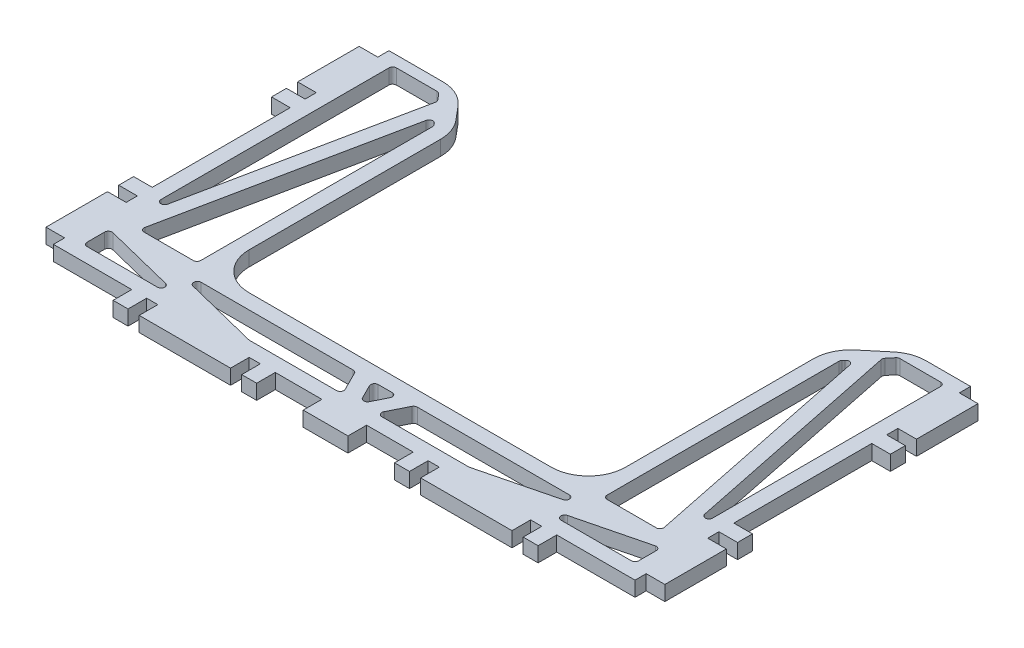
SolidWorks part; units mm, degrees
ref_plane "Front Plane" through (0, 0, 0) normal (0, 0, 1) x (1, 0, 0)
ref_plane "Top Plane" through (0, 0, 0) normal (0, 1, 0) x (1, 0, 0)
ref_plane "Right Plane" through (0, 0, 0) normal (1, 0, 0) x (0, 0, -1)
sketch "Sketch1" plane through (0, 0, 0) normal (0, 1, 0) x (1, 0, 0)
  line L0 (-78, 42.5) -> (-58.891, 42.5)
  line L1 (-58.891, 42.5) -> (-50.5, 32.5)
  line L2 (-50.5, 32.5) -> (-50.5, -32.5)
  line L3 (-50.5, -32.5) -> (50.5, -32.5)
  line L4 (50.5, -32.5) -> (50.5, 32.5)
  line L5 (50.5, 32.5) -> (62.4175, 42.5)
  line L6 (62.4175, 42.5) -> (78, 42.5)
  line L7 (78, 42.5) -> (78, -47.5)
  line L8 (78, -47.5) -> (-78, -47.5)
  line L9 (-78, -47.5) -> (-78, 42.5)
  line L10 (0, 42.5) -> (0, -47.5) construction
  line L11 (78, 39.5) -> (83, 39.5)
  line L12 (78, 39.5) -> (78, 23)
  line L13 (78, 23) -> (83, 23)
  line L14 (83, 39.5) -> (83, 23)
  line L15 (78, -28) -> (83, -28)
  line L16 (78, -28) -> (78, -44.5)
  line L17 (78, -44.5) -> (83, -44.5)
  line L18 (83, -28) -> (83, -44.5)
  line L19 (-6, -47.5) -> (-6, -52.5)
  line L20 (78, 20) -> (83, 20)
  line L21 (78, 20) -> (78, 16)
  line L22 (78, 16) -> (83, 16)
  line L23 (83, 20) -> (83, 16)
  line L24 (78, -25) -> (83, -25)
  line L25 (78, -25) -> (78, -21)
  line L26 (78, -21) -> (83, -21)
  line L27 (83, -25) -> (83, -21)
  line L28 (25.5, -47.5) -> (50, -47.5)
  line L29 (25.5, -47.5) -> (25.5, -52.5)
  line L30 (25.5, -52.5) -> (50, -52.5)
  line L31 (50, -47.5) -> (50, -52.5)
  line L32 (53, -47.5) -> (57, -47.5)
  line L33 (53, -47.5) -> (53, -52.5)
  line L34 (53, -52.5) -> (57, -52.5)
  line L35 (57, -47.5) -> (57, -52.5)
  line L36 (22.5, -47.5) -> (18.5, -47.5)
  line L37 (22.5, -47.5) -> (22.5, -52.5)
  line L38 (22.5, -52.5) -> (18.5, -52.5)
  line L39 (18.5, -47.5) -> (18.5, -52.5)
  line L40 (-6, -47.5) -> (6, -47.5)
  line L41 (0, -47.5) -> (0, -52.5)
  line L42 (-6, -52.5) -> (6, -52.5)
  line L43 (6, -47.5) -> (6, -52.5)
  line L44 (-22.5, -52.5) -> (-18.5, -52.5)
  line L45 (-18.5, -47.5) -> (-18.5, -52.5)
  line L46 (-22.5, -47.5) -> (-18.5, -47.5)
  line L47 (-22.5, -47.5) -> (-22.5, -52.5)
  line L48 (-25.5, -52.5) -> (-50, -52.5)
  line L49 (-50, -47.5) -> (-50, -52.5)
  line L50 (-25.5, -47.5) -> (-50, -47.5)
  line L51 (-25.5, -47.5) -> (-25.5, -52.5)
  line L52 (-53, -52.5) -> (-57, -52.5)
  line L53 (-57, -47.5) -> (-57, -52.5)
  line L54 (-53, -47.5) -> (-57, -47.5)
  line L55 (-53, -47.5) -> (-53, -52.5)
  line L56 (-78, -44.5) -> (-83, -44.5)
  line L57 (-83, -28) -> (-83, -44.5)
  line L58 (-78, -28) -> (-83, -28)
  line L59 (-78, -28) -> (-78, -44.5)
  line L60 (-78, -21) -> (-83, -21)
  line L61 (-83, -25) -> (-83, -21)
  line L62 (-78, -25) -> (-83, -25)
  line L63 (-78, -25) -> (-78, -21)
  line L64 (-78, 16) -> (-83, 16)
  line L65 (-83, 20) -> (-83, 16)
  line L66 (-78, 20) -> (-83, 20)
  line L67 (-78, 20) -> (-78, 16)
  line L68 (-78, 23) -> (-83, 23)
  line L69 (-83, 39.5) -> (-83, 23)
  line L70 (-78, 39.5) -> (-83, 39.5)
  line L71 (-78, 39.5) -> (-78, 23)
  line L72 (-74, 39.5) -> (-61.5953, 39.5)
  line L73 (-61.5953, 39.5) -> (-59.6881, 37.227)
  line L74 (-59.6881, 37.227) -> (-74, -32.5)
  line L75 (-74, -32.5) -> (-74, 39.5)
  line L76 (-56.4072, 33.3171) -> (-54.5, 31.0441)
  line L77 (-54.5, 31.0441) -> (-54.5, -32.5)
  line L78 (-54.5, -32.5) -> (-69.9166, -32.5)
  line L79 (-69.9166, -32.5) -> (-56.4072, 33.3171)
  line L80 (-74, -36.5) -> (-74, -43.5)
  line L81 (-74, -43.5) -> (-45.997, -43.5)
  line L82 (-45.997, -43.5) -> (-74, -36.5)
  line L83 (-57.5059, -36.5) -> (-7.9721, -36.5)
  line L84 (-7.9721, -36.5) -> (-4.4721, -43.5)
  line L85 (-4.4721, -43.5) -> (-29.503, -43.5)
  line L86 (-29.503, -43.5) -> (-57.5059, -36.5)
  line L89 (0, -36.5) -> (0, -43.5)
  line L90 (-45.997, -43.5) -> (-29.503, -43.5) construction
  line L91 (3.5, -36.5) -> (-3.5, -36.5)
  line L92 (-3.5, -36.5) -> (0, -43.5)
  line L93 (3.5, -36.5) -> (0, -43.5)
  line L94 (4.4721, -43.5) -> (29.503, -43.5)
  line L95 (7.9721, -36.5) -> (4.4721, -43.5)
  line L96 (57.5059, -36.5) -> (7.9721, -36.5)
  line L97 (29.503, -43.5) -> (57.5059, -36.5)
  line L98 (74, -43.5) -> (45.997, -43.5)
  line L99 (74, -36.5) -> (74, -43.5)
  line L100 (45.997, -43.5) -> (74, -36.5)
  line L101 (54.5, -32.5) -> (69.9166, -32.5)
  line L102 (54.5, 31.0441) -> (54.5, -32.5)
  line L103 (56.4072, 33.3171) -> (54.5, 31.0441)
  line L104 (69.9166, -32.5) -> (56.4072, 33.3171)
  line L105 (59.6881, 37.227) -> (74, -32.5)
  line L106 (61.5953, 39.5) -> (59.6881, 37.227)
  line L107 (74, 39.5) -> (61.5953, 39.5)
  line L108 (74, -32.5) -> (74, 39.5)
  point P8 (0, -47.5)
  point P12 (0, -32.5)
  point P18 (50.5, 0)
  point P92 (-37.75, -43.5)
  point P93 (0, 0)
  point P96 (-37.75, -52.5)
  point P97 (-8.3743, -36.5)
  dimension "D1" = 90
  dimension "D2" = 156
  dimension "D3" = 27.5
  dimension "D4" = 15
  dimension "D5" = 65
  dimension "D6" = 50
  dimension "D7" = 16.5
  dimension "D8" = 3
  dimension "D9" = 3
  dimension "D10" = 3
  dimension "D11" = 3
  dimension "D12" = 4
  dimension "D13" = 5
  dimension "D14" = 5
  dimension "D15" = 28
  dimension "D16" = 24.5
  dimension "D17" = 3
  dimension "D18" = 3
  dimension "D19" = 4
  dimension "D20" = 6
  dimension "D21" = 4
  dimension "D22" = 4
  dimension "D23" = 4
  dimension "D24" = 4
  dimension "D25" = 4
  dimension "D26" = 4
  dimension "D27" = 4
  dimension "D28" = 4
  dimension "D29" = 3.5
extrude "Boss-Extrude1" add sketch "Sketch1" along normal blind 4 contours L9 L8 L40 L7 L6 L5 L4 L3 L2 L1 L0 L108 L105 L106 L107 L104 L101 L102 L103 | L9 L70 L69 L68 | L9 L66 L65 L64 | L62 L9 L60 L61 | L9 L58 L57 L56 | L55 L8 L53 L52 | L51 L8 L49 L48 | L8 L47 L44 L45 | L19 L42 L41 L40 | L43 L8 L41 L42 | L8 L39 L38 L37 | L31 L8 L29 L30 | L35 L8 L33 L34 | L18 L15 L7 L17 | L24 L27 L26 L7 | L14 L11 L7 L13 | L23 L20 L7 L22
fillet "Fillet1" radius 10 6 edges at (62.4175, 2, -42.5) (50.5, 2, -32.5) (-50.5, 2, -32.5) (-58.891, 2, -42.5) (50.5, 2, 32.5) (-50.5, 2, 32.5)
fillet "Fillet2" radius 1 33 edges at (-54.5, 2, 32.5) (59.6881, 2, -37.227) (74, 2, -39.5) (56.4072, 2, -33.3171) (61.5953, 2, -39.5) (54.5, 2, -31.0441) (69.9166, 2, 32.5) (74, 2, 32.5) (54.5, 2, 32.5) (45.997, 2, 43.5) (74, 2, 43.5) (74, 2, 36.5) (57.5059, 2, 36.5) (4.4721, 2, 43.5) (7.9721, 2, 36.5) (-3.5, 2, 36.5) (0, 2, 43.5) (-29.503, 2, 43.5) (3.5, 2, 36.5) (-7.9721, 2, 36.5) (29.503, 2, 43.5) (-4.4721, 2, 43.5) (-45.997, 2, 43.5) (-57.5059, 2, 36.5) (-74, 2, 36.5) (-69.9166, 2, 32.5) (-74, 2, 43.5) (-74, 2, 32.5) (-74, 2, -39.5) (-56.4072, 2, -33.3171) (-54.5, 2, -31.0441) (-59.6881, 2, -37.227) (-61.5953, 2, -39.5)
